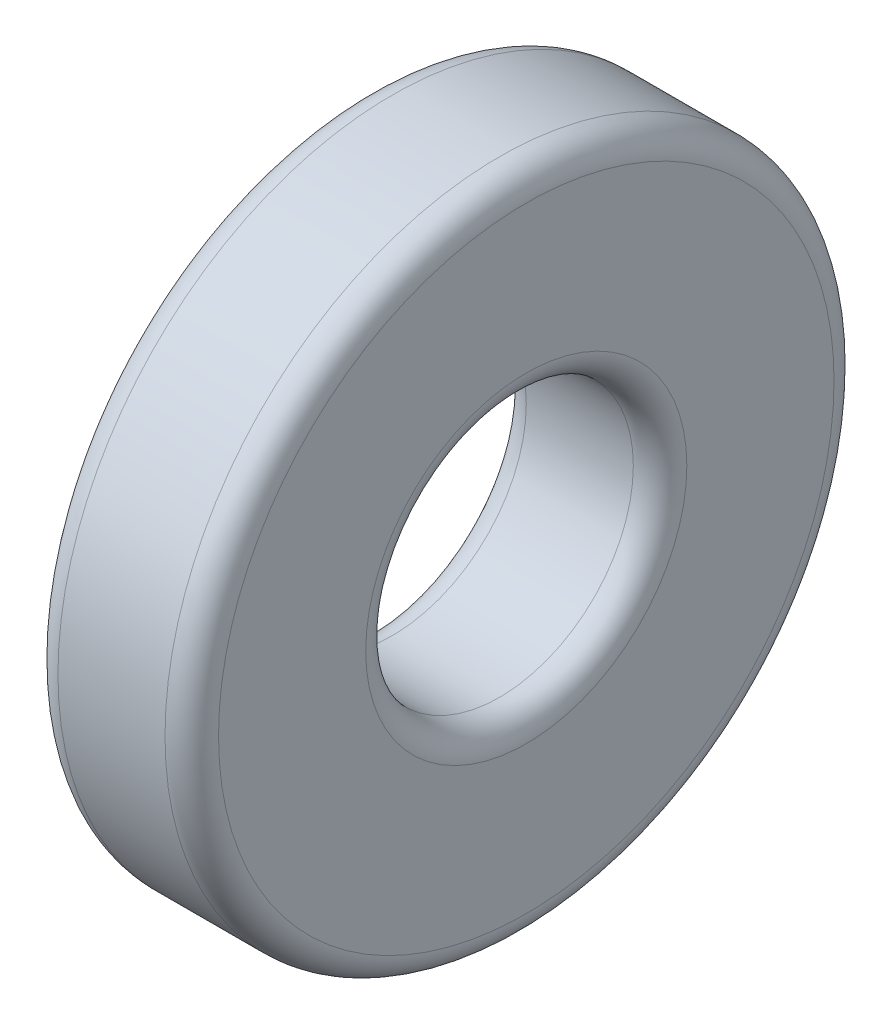
SolidWorks part; units mm, degrees
ref_plane "Front Plane" through (0, 0, 0) normal (1, 0, 0) x (0, 1, 0)
ref_plane "Top Plane" through (0, 0, 0) normal (0, 0, 1) x (0, 1, 0)
ref_plane "Right Plane" through (0, 0, 0) normal (0, 1, 0) x (-1, 0, 0)
sketch "Sketch1" plane through (0, 0, 0) normal (0, 1, 0) x (-1, 0, 0)
  line L0 (2, 12.5) -> (-2, 12.5)
  line L1 (-3, 11.5) -> (-3, 6)
  line L2 (-2, 5) -> (2, 5)
  line L3 (3, 11.5) -> (3, 6)
  line L4 (3.1111, 0) -> (27.3333, 0) construction
  arc A0 (2, 5) -> (3, 6) centre (2, 6) ccw
  arc A1 (-3, 6) -> (-2, 5) centre (-2, 6) ccw
  arc A2 (-2, 12.5) -> (-3, 11.5) centre (-2, 11.5) ccw
  arc A3 (2, 12.5) -> (3, 11.5) centre (2, 11.5) cw
  point P3 (0, 5)
  point P15 (-3, 12.5)
  point P18 (3, 12.5)
  dimension "D4" = 1
  dimension "D1" = 10
  dimension "D2" = 25
  dimension "D3" = 6
revolve "Revolve1" add sketch "Sketch1" angle 360 about L4
